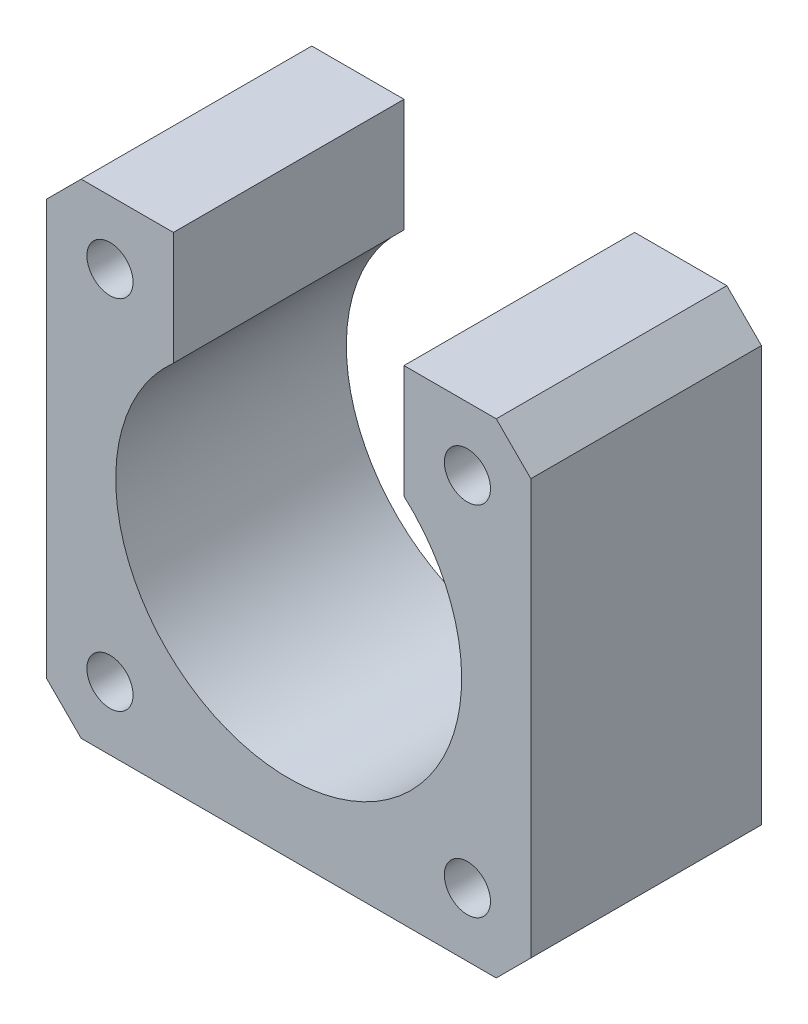
SolidWorks part; units mm, degrees
ref_plane "前视基准面" through (0, 0, 0) normal (0, 0, 1) x (1, 0, 0)
ref_plane "上视基准面" through (0, 0, 0) normal (0, 1, 0) x (1, 0, 0)
ref_plane "右视基准面" through (0, 0, 0) normal (1, 0, 0) x (0, 0, -1)
sketch "草图1" plane through (0, 0, 0) normal (0, 0, 1) x (1, 0, 0)
  line L0 (-21, 18) -> (-18, 21)
  line L1 (-18, -21) -> (18, -21)
  line L2 (-21, -18) -> (-21, 18)
  line L3 (-18, 21) -> (-10, 21)
  line L4 (21, -18) -> (21, 18)
  line L5 (-21, -21) -> (21, 21) construction
  line L6 (-21, 21) -> (21, -21) construction
  line L7 (-21, -18) -> (-18, -21)
  line L8 (18, -21) -> (21, -18)
  line L9 (18, 21) -> (21, 18)
  line L10 (-10, 21) -> (-10, 11.1803)
  line L11 (10, 21) -> (10, 11.1803)
  line L12 (10, 21) -> (18, 21)
  arc A0 (-10, 11.1803) -> (10, 11.1803) centre (0, 0) ccw
  circle A1 centre (15.5, 15.5) radius 2
  circle A2 centre (15.5, -15.5) radius 2
  circle A3 centre (-15.5, -15.5) radius 2
  circle A4 centre (-15.5, 15.5) radius 2
  point P0 (0, 0)
  point P18 (0, 0)
  dimension "D3" = 30
  dimension "D4" = 4
  dimension "D1" = 42
  dimension "D2" = 42
  dimension "D6" = 31
  dimension "D7" = 20
  dimension "D5" = 4
extrude "凸台-拉伸1" add sketch "草图1" along normal blind 20
